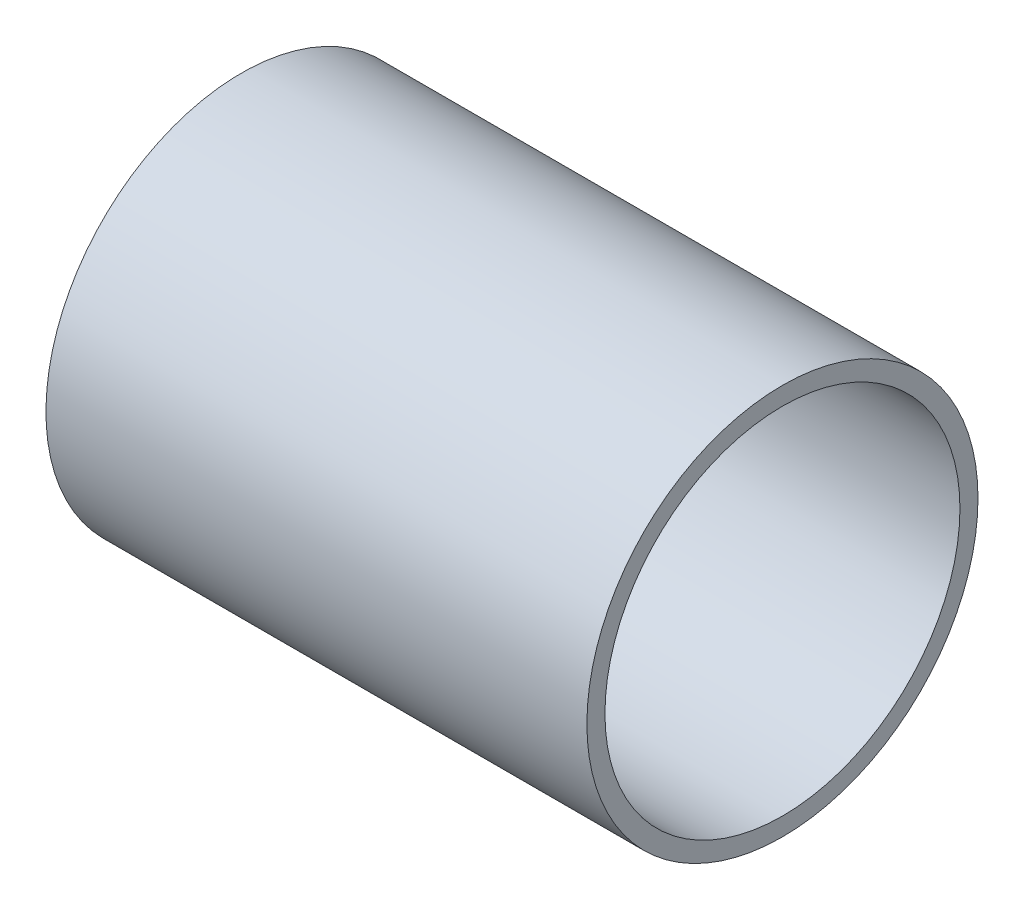
SolidWorks part; units mm, degrees
ref_plane "Front Plane" through (0, 0, 0) normal (0, 0, 1) x (1, 0, 0)
ref_plane "Top Plane" through (0, 0, 0) normal (0, 1, 0) x (1, 0, 0)
ref_plane "Right Plane" through (0, 0, 0) normal (1, 0, 0) x (0, 0, -1)
sketch "Sketch1" plane through (0, 0, 0) normal (1, 0, 0) x (0, 0, -1)
  circle A0 centre (0, 0) radius 32.5
  dimension "D1" = 65
extrude "Extrude-Thin1" add sketch "Sketch1" along normal up to surface (44.7 mm away) and the other way up to surface (45.2 mm away) thin thin type one direction reverse wall 3
sketch "Sketch2" plane through (0, 0, 0) normal (1, 0, 0) x (0, 0, -1)
  point P0 (0, 0)
